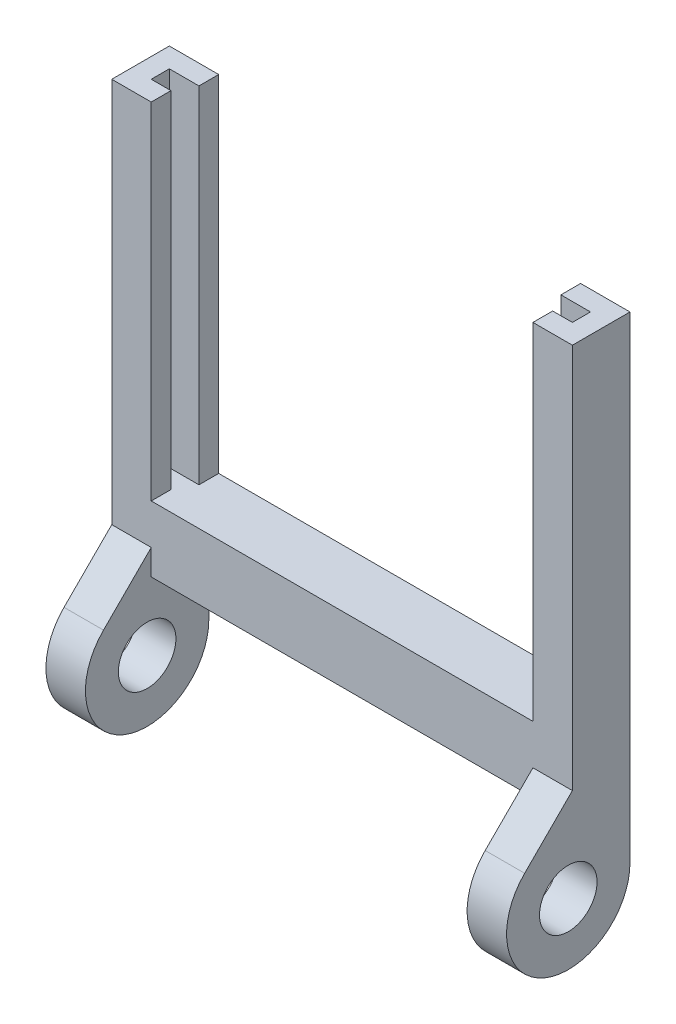
SolidWorks part; units mm, degrees
material "S235JR"
ref_plane "Piano X" through (0, 0, 0) normal (0, 0, 1) x (1, 0, 0)
ref_plane "Piano Y" through (0, 0, 0) normal (0, 1, 0) x (1, 0, 0)
ref_plane "Piano Z" through (0, 0, 0) normal (1, 0, 0) x (0, 0, -1)
sketch "Schizzo1" plane through (0, 0, 0) normal (0, 0, 1) x (1, 0, 0)
  line L1 (-14, -12.5) -> (14, -12.5)
  line L2 (-14, -12.5) -> (-14, 12.5)
  line L3 (-14, 12.5) -> (14, 12.5)
  line L4 (14, -12.5) -> (14, 12.5)
  line L5 (0, 12.5) -> (0, -12.5) construction
  line L6 (-14, 0) -> (14, 0) construction
  point P0 (0, 0)
  point P2 (0, 0.85)
  point P4 (0, -15.4633)
  dimension "D1" = 28
  dimension "D2" = 25
extrude "Estrusione-Estrusione1" add sketch "Schizzo1" along normal blind 1.2
sketch "Schizzo4" plane through (0, 0, 1.2) normal (0, 0, 1) x (1, 0, 0)
  line L0 (14, 12.5) -> (-14, 12.5) construction
  line L1 (-11, 12.5) -> (11, 12.5)
  line L2 (-11, 12.5) -> (-11, -8.5)
  line L3 (-11, -8.5) -> (11, -8.5)
  line L4 (11, 12.5) -> (11, -8.5)
  line L5 (0, 0) -> (0, 12.5) construction
  line L6 (-14, -12.5) -> (14, -12.5) construction
  line L7 (-14, 12.5) -> (-14, -12.5) construction
  dimension "D1" = 4
  dimension "D2" = 3
extrude "Taglio-Estrusione1" cut sketch "Schizzo4" against normal through all
sketch "Schizzo2" plane through (14, 0, 0) normal (1, 0, 0) x (0, 0, -1)
  line L0 (0, -12.5) -> (0, -16.5)
  line L1 (0, -12.5) -> (-1.2, -12.5)
  line L2 (-6.4017, -13.8483) -> (-3.2, -10.6467)
  line L5 (-1.2, -12.5) -> (-1.2, -10.6467)
  line L6 (-1.2, -12.5) -> (-1.2, 12.5) construction
  line L7 (-1.2, -10.6467) -> (-3.2, -10.6467)
  arc A0 (-6.4017, -13.8483) -> (0, -16.5) centre (-3.75, -16.5) ccw
  circle A1 centre (-3.75, -16.5) radius 1.75
  point P1 (-3.75, -8.5329)
  dimension "D2" = 3.5
  dimension "D1" = 2
  dimension "D3" = 4
  dimension "D4" = 135
  dimension "D5" = 2
extrude "Estrusione-Estrusione2" add sketch "Schizzo2" against normal blind 2.4
sketch "Schizzo3" plane through (0, 12.5, 0) normal (0, 1, 0) x (1, 0, 0)
  line L0 (14, -1.2) -> (14, -3.5)
  line L1 (14, -3.5) -> (11.6, -3.5)
  line L2 (11.6, -3.5) -> (11.6, -2.3)
  line L3 (11.6, -2.3) -> (12.8, -2.3)
  line L4 (12.8, -2.3) -> (12.8, -1.2)
  line L6 (12.8, -1.2) -> (14, -1.2)
  line L8 (-11, -1.2) -> (11, -1.2) construction
  point P3 (13.5, -2)
  point P8 (4.3209, -9.7756)
  point P9 (17.8968, -2)
  point P10 (9.2829, -2.5276)
  point P12 (13.5, -2)
  dimension "D1" = 1.2
  dimension "D2" = 1.1
  dimension "D3" = 1.2
  dimension "D4" = 1.2
extrude "Estrusione-Estrusione3" add sketch "Schizzo3" against normal up to surface (23.1467 mm away) up to face at (12.8, -10.6467, 2.2)
mirror "Specchia1" about plane through (0, 0, 0) normal (1, 0, 0) of "Estrusione-Estrusione3", "Estrusione-Estrusione2"
sketch "Schizzo5" plane through (0, 0, 1.2) normal (0, 0, 1) x (1, 0, 0)
  line L0 (-14, -10.6467) -> (-14, 12.5) construction
  line L1 (-14, -12.5) -> (14, -12.5)
  line L2 (-14, -12.5) -> (-14, -8.5)
  line L3 (-14, -8.5) -> (14, -8.5)
  line L4 (14, -12.5) -> (14, -8.5)
  line L5 (14, -10.6467) -> (14, 12.5) construction
  line L6 (-11.6, -12.5) -> (11.6, -12.5) construction
  line L7 (-11, -8.5) -> (11, -8.5) construction
  point P8 (13.5, -9.4306)
  point P11 (0, 0)
  point P12 (0, 0)
extrude "Estrusione-Estrusione4" add sketch "Schizzo5" along normal up to surface (2.3 mm away) up to face at (-12.8, 0.9267, 3.5)
equation "\"D1@Schizzo2\"=0.4 *5"
